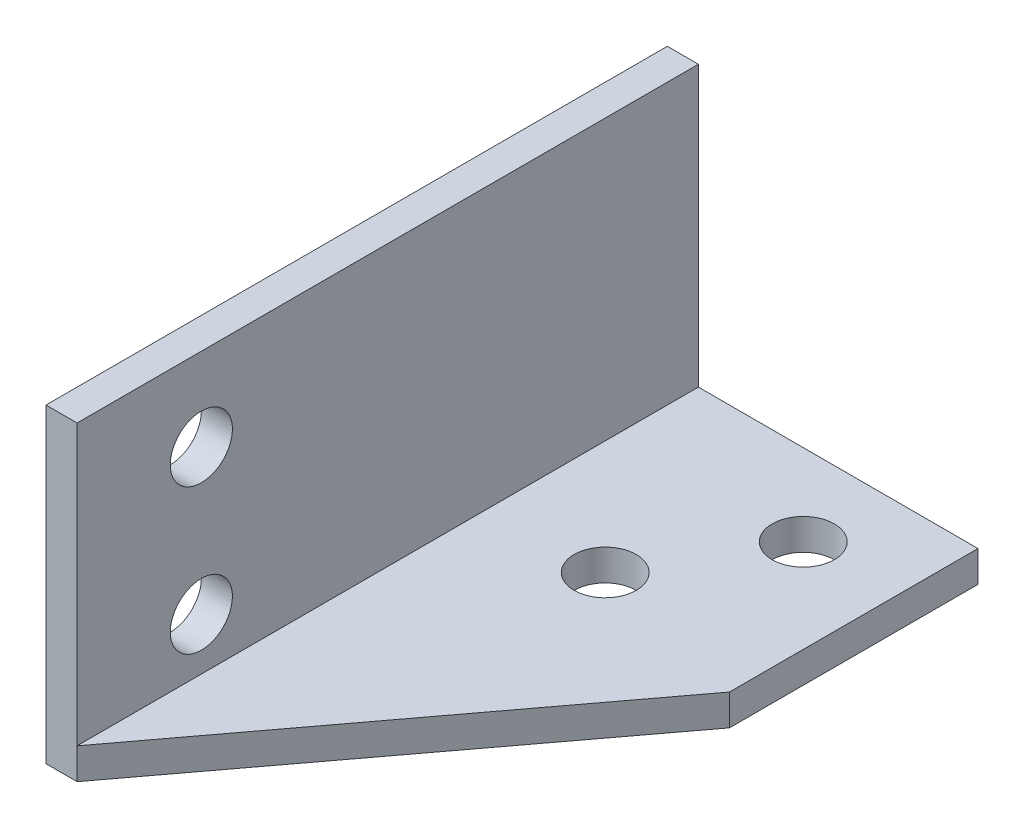
SolidWorks part; units mm, degrees
ref_plane "Plan de face" through (0, 0, 0) normal (0, 0, 1) x (1, 0, 0)
ref_plane "Plan de dessus" through (0, 0, 0) normal (0, 1, 0) x (1, 0, 0)
ref_plane "Plan de droite" through (0, 0, 0) normal (1, 0, 0) x (0, 0, -1)
sketch "Esquisse1" plane through (0, 0, 0) normal (0, 0, 1) x (1, 0, 0)
  line L0 (-9.773, -6.59) -> (-8.273, -6.59)
  line L1 (-8.273, -6.59) -> (-8.273, -20.09)
  line L2 (-8.273, -20.09) -> (5.227, -20.09)
  line L3 (5.227, -20.09) -> (5.227, -21.59)
  line L4 (5.227, -21.59) -> (-9.773, -21.59)
  line L5 (-9.773, -21.59) -> (-9.773, -6.59)
  dimension "D1" = 1.5
  dimension "D2" = 1.5
  dimension "D3" = 15
  dimension "D4" = 15
extrude "Extrusion1" add sketch "Esquisse1" along normal blind 30
sketch "Esquisse3" plane through (-8.273, 0, 0) normal (1, 0, 0) x (0, 0, -1)
  line L0 (-30, -6.59) -> (0, -6.59) construction
  line L1 (-30, -20.09) -> (-30, -6.59) construction
  circle A0 centre (-24, -10.59) radius 1.5
  circle A1 centre (-24, -17.59) radius 1.5
  dimension "D1" = 7
  dimension "D2" = 4
  dimension "D3" = 6
  dimension "D4" = 6
extrude "Extrusion2" cut sketch "Esquisse3" against normal blind 60
sketch "Esquisse4" plane through (0, -20.09, 0) normal (0, 1, 0) x (-1, 0, 0)
  line L0 (-5.227, 0) -> (8.273, 0) construction
  line L1 (-5.227, 30) -> (-5.227, 0) construction
  line L2 (-5.227, 30) -> (8.273, 30)
  line L3 (8.273, 30) -> (-5.227, 12)
  line L4 (-5.227, 12) -> (-5.227, 30)
  circle A0 centre (2.773, 10) radius 1.5
  circle A1 centre (2.773, 10) radius 7 construction
  circle A2 centre (-0.727, 3.9378) radius 1.5
  dimension "D1" = 10
  dimension "D4" = 14
  dimension "D5" = 18
  dimension "D2" = 8
  dimension "D3" = 4.5
extrude "Extrusion3" cut sketch "Esquisse4" against normal blind 60
